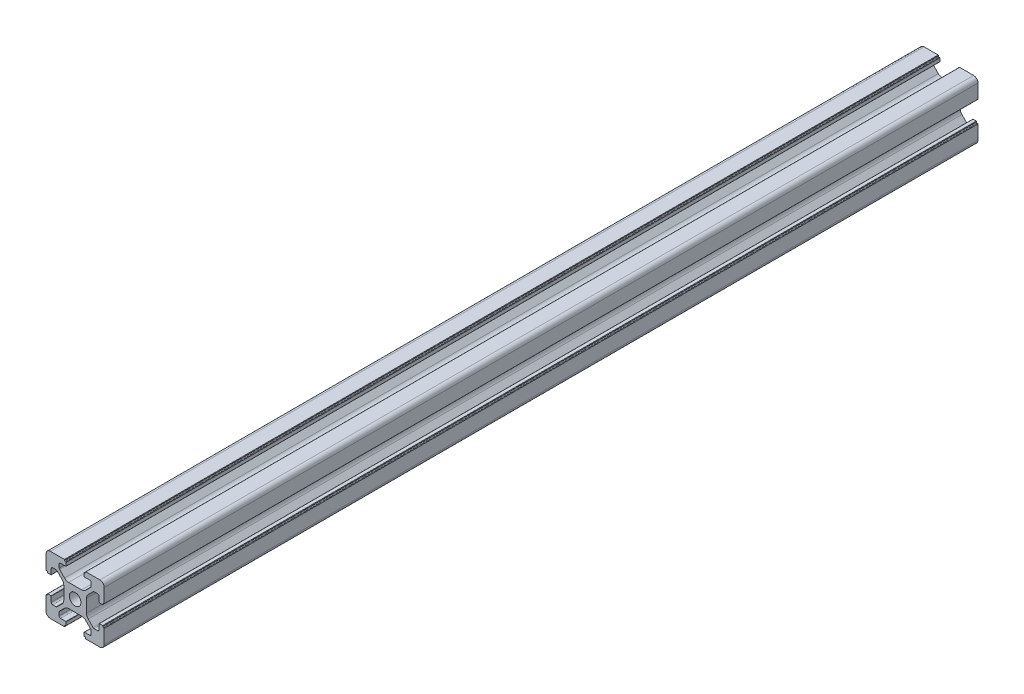
SolidWorks part; units mm, degrees
ref_plane "Plan de face" through (0, 0, 0) normal (0, 0, 1) x (1, 0, 0)
ref_plane "Plan de dessus" through (0, 0, 0) normal (0, 1, 0) x (1, 0, 0)
ref_plane "Plan de droite" through (0, 0, 0) normal (1, 0, 0) x (0, 0, -1)
sketch "Esquisse2" plane through (0, 0, 0) normal (0, 0, 1) x (1, 0, 0)
  line L0 (10, -8.5) -> (10, -3.7)
  line L1 (9.9, -3.6) -> (9.7, -3.6)
  line L2 (9.5, -3.4) -> (9.5, -3.2)
  line L3 (9.4, -3.1) -> (8.3, -3.1)
  line L4 (8.2, -3.2) -> (8.2, -5)
  line L5 (7.7, -5.5) -> (6.5556, -5.5)
  line L6 (6.2021, -5.3536) -> (4.4858, -3.6373)
  line L7 (3.9, -2.223) -> (3.9, 2.223)
  line L8 (4.4858, 3.6373) -> (6.2021, 5.3536)
  line L9 (6.5556, 5.5) -> (7.7, 5.5)
  line L10 (8.2, 5) -> (8.2, 3.2)
  line L11 (8.3, 3.1) -> (9.4, 3.1)
  line L12 (9.5, 3.2) -> (9.5, 3.4)
  line L13 (9.7, 3.6) -> (9.9, 3.6)
  line L14 (10, 3.7) -> (10, 8.5)
  line L15 (8.5, 10) -> (3.7, 10)
  line L16 (3.6, 9.9) -> (3.6, 9.7)
  line L17 (3.4, 9.5) -> (3.2, 9.5)
  line L18 (3.1, 9.4) -> (3.1, 8.3)
  line L19 (3.2, 8.2) -> (5, 8.2)
  line L20 (5.5, 7.7) -> (5.5, 6.5556)
  line L21 (5.3536, 6.2021) -> (3.6373, 4.4858)
  line L22 (2.223, 3.9) -> (-2.223, 3.9)
  line L23 (-3.6373, 4.4858) -> (-5.3536, 6.2021)
  line L24 (-5.5, 6.5556) -> (-5.5, 7.7)
  line L25 (-5, 8.2) -> (-3.2, 8.2)
  line L26 (-3.1, 8.3) -> (-3.1, 9.4)
  line L27 (-3.2, 9.5) -> (-3.4, 9.5)
  line L28 (-3.6, 9.7) -> (-3.6, 9.9)
  line L29 (-3.7, 10) -> (-8.5, 10)
  line L30 (-10, 8.5) -> (-10, 3.7)
  line L31 (-9.9, 3.6) -> (-9.7, 3.6)
  line L32 (-9.5, 3.4) -> (-9.5, 3.2)
  line L33 (-9.4, 3.1) -> (-8.3, 3.1)
  line L34 (-8.2, 3.2) -> (-8.2, 5)
  line L35 (-7.7, 5.5) -> (-6.5556, 5.5)
  line L36 (-6.2021, 5.3536) -> (-4.4858, 3.6373)
  line L37 (-3.9, 2.223) -> (-3.9, -2.223)
  line L38 (-4.4858, -3.6373) -> (-6.2021, -5.3536)
  line L39 (-6.5556, -5.5) -> (-7.7, -5.5)
  line L40 (-8.2, -5) -> (-8.2, -3.2)
  line L41 (-8.3, -3.1) -> (-9.4, -3.1)
  line L42 (-9.5, -3.2) -> (-9.5, -3.4)
  line L43 (-9.7, -3.6) -> (-9.9, -3.6)
  line L44 (-10, -3.7) -> (-10, -8.5)
  line L45 (-8.5, -10) -> (-3.7, -10)
  line L46 (-3.6, -9.9) -> (-3.6, -9.7)
  line L47 (-3.4, -9.5) -> (-3.2, -9.5)
  line L48 (-3.1, -9.4) -> (-3.1, -8.3)
  line L49 (-3.2, -8.2) -> (-5, -8.2)
  line L50 (-5.5, -7.7) -> (-5.5, -6.5556)
  line L51 (-5.3536, -6.2021) -> (-3.6373, -4.4858)
  line L52 (-2.223, -3.9) -> (2.223, -3.9)
  line L53 (3.6373, -4.4858) -> (5.3536, -6.2021)
  line L54 (5.5, -6.5556) -> (5.5, -7.7)
  line L55 (5, -8.2) -> (3.2, -8.2)
  line L56 (3.1, -8.3) -> (3.1, -9.4)
  line L57 (3.2, -9.5) -> (3.4, -9.5)
  line L58 (3.6, -9.7) -> (3.6, -9.9)
  line L59 (3.7, -10) -> (8.5, -10)
  arc A0 (8.5, -10) -> (10, -8.5) centre (8.5, -8.5) ccw
  arc A1 (10, -3.7) -> (9.9, -3.6) centre (9.9, -3.7) ccw
  arc A2 (9.5, -3.4) -> (9.7, -3.6) centre (9.7, -3.4) ccw
  arc A3 (9.5, -3.2) -> (9.4, -3.1) centre (9.4, -3.2) ccw
  arc A4 (8.3, -3.1) -> (8.2, -3.2) centre (8.3, -3.2) ccw
  arc A5 (7.7, -5.5) -> (8.2, -5) centre (7.7, -5) ccw
  arc A6 (6.2021, -5.3536) -> (6.5556, -5.5) centre (6.5556, -5) ccw
  arc A7 (3.9, -2.223) -> (4.4858, -3.6373) centre (5.9, -2.223) ccw
  arc A8 (4.4858, 3.6373) -> (3.9, 2.223) centre (5.9, 2.223) ccw
  arc A9 (6.5556, 5.5) -> (6.2021, 5.3536) centre (6.5556, 5) ccw
  arc A10 (8.2, 5) -> (7.7, 5.5) centre (7.7, 5) ccw
  arc A11 (8.2, 3.2) -> (8.3, 3.1) centre (8.3, 3.2) ccw
  arc A12 (9.4, 3.1) -> (9.5, 3.2) centre (9.4, 3.2) ccw
  arc A13 (9.7, 3.6) -> (9.5, 3.4) centre (9.7, 3.4) ccw
  arc A14 (9.9, 3.6) -> (10, 3.7) centre (9.9, 3.7) ccw
  arc A15 (10, 8.5) -> (8.5, 10) centre (8.5, 8.5) ccw
  arc A16 (3.7, 10) -> (3.6, 9.9) centre (3.7, 9.9) ccw
  arc A17 (3.4, 9.5) -> (3.6, 9.7) centre (3.4, 9.7) ccw
  arc A18 (3.2, 9.5) -> (3.1, 9.4) centre (3.2, 9.4) ccw
  arc A19 (3.1, 8.3) -> (3.2, 8.2) centre (3.2, 8.3) ccw
  arc A20 (5.5, 7.7) -> (5, 8.2) centre (5, 7.7) ccw
  arc A21 (5.3536, 6.2021) -> (5.5, 6.5556) centre (5, 6.5556) ccw
  arc A22 (2.223, 3.9) -> (3.6373, 4.4858) centre (2.223, 5.9) ccw
  arc A23 (-3.6373, 4.4858) -> (-2.223, 3.9) centre (-2.223, 5.9) ccw
  arc A24 (-5.5, 6.5556) -> (-5.3536, 6.2021) centre (-5, 6.5556) ccw
  arc A25 (-5, 8.2) -> (-5.5, 7.7) centre (-5, 7.7) ccw
  arc A26 (-3.2, 8.2) -> (-3.1, 8.3) centre (-3.2, 8.3) ccw
  arc A27 (-3.1, 9.4) -> (-3.2, 9.5) centre (-3.2, 9.4) ccw
  arc A28 (-3.6, 9.7) -> (-3.4, 9.5) centre (-3.4, 9.7) ccw
  arc A29 (-3.6, 9.9) -> (-3.7, 10) centre (-3.7, 9.9) ccw
  arc A30 (-8.5, 10) -> (-10, 8.5) centre (-8.5, 8.5) ccw
  arc A31 (-10, 3.7) -> (-9.9, 3.6) centre (-9.9, 3.7) ccw
  arc A32 (-9.5, 3.4) -> (-9.7, 3.6) centre (-9.7, 3.4) ccw
  arc A33 (-9.5, 3.2) -> (-9.4, 3.1) centre (-9.4, 3.2) ccw
  arc A34 (-8.3, 3.1) -> (-8.2, 3.2) centre (-8.3, 3.2) ccw
  arc A35 (-7.7, 5.5) -> (-8.2, 5) centre (-7.7, 5) ccw
  arc A36 (-6.2021, 5.3536) -> (-6.5556, 5.5) centre (-6.5556, 5) ccw
  arc A37 (-3.9, 2.223) -> (-4.4858, 3.6373) centre (-5.9, 2.223) ccw
  arc A38 (-4.4858, -3.6373) -> (-3.9, -2.223) centre (-5.9, -2.223) ccw
  arc A39 (-6.5556, -5.5) -> (-6.2021, -5.3536) centre (-6.5556, -5) ccw
  arc A40 (-8.2, -5) -> (-7.7, -5.5) centre (-7.7, -5) ccw
  arc A41 (-8.2, -3.2) -> (-8.3, -3.1) centre (-8.3, -3.2) ccw
  arc A42 (-9.4, -3.1) -> (-9.5, -3.2) centre (-9.4, -3.2) ccw
  arc A43 (-9.7, -3.6) -> (-9.5, -3.4) centre (-9.7, -3.4) ccw
  arc A44 (-9.9, -3.6) -> (-10, -3.7) centre (-9.9, -3.7) ccw
  arc A45 (-10, -8.5) -> (-8.5, -10) centre (-8.5, -8.5) ccw
  arc A46 (-3.7, -10) -> (-3.6, -9.9) centre (-3.7, -9.9) ccw
  arc A47 (-3.4, -9.5) -> (-3.6, -9.7) centre (-3.4, -9.7) ccw
  arc A48 (-3.2, -9.5) -> (-3.1, -9.4) centre (-3.2, -9.4) ccw
  arc A49 (-3.1, -8.3) -> (-3.2, -8.2) centre (-3.2, -8.3) ccw
  arc A50 (-5.5, -7.7) -> (-5, -8.2) centre (-5, -7.7) ccw
  arc A51 (-5.3536, -6.2021) -> (-5.5, -6.5556) centre (-5, -6.5556) ccw
  arc A52 (-2.223, -3.9) -> (-3.6373, -4.4858) centre (-2.223, -5.9) ccw
  arc A53 (3.6373, -4.4858) -> (2.223, -3.9) centre (2.223, -5.9) ccw
  arc A54 (5.5, -6.5556) -> (5.3536, -6.2021) centre (5, -6.5556) ccw
  arc A55 (5, -8.2) -> (5.5, -7.7) centre (5, -7.7) ccw
  arc A56 (3.2, -8.2) -> (3.1, -8.3) centre (3.2, -8.3) ccw
  arc A57 (3.1, -9.4) -> (3.2, -9.5) centre (3.2, -9.4) ccw
  arc A58 (3.6, -9.7) -> (3.4, -9.5) centre (3.4, -9.7) ccw
  arc A59 (3.6, -9.9) -> (3.7, -10) centre (3.7, -9.9) ccw
extrude "Boss.-Extru.2" add sketch "Esquisse2" along normal blind 300
sketch "Esquisse3" plane through (0, 0, 0) normal (0, 0, -1) x (-1, 0, 0)
  circle A0 centre (0, 0) radius 2
  dimension "D1" = 4
extrude "Enlèv. mat.-Extru.1" cut sketch "Esquisse3" against normal blind 300
